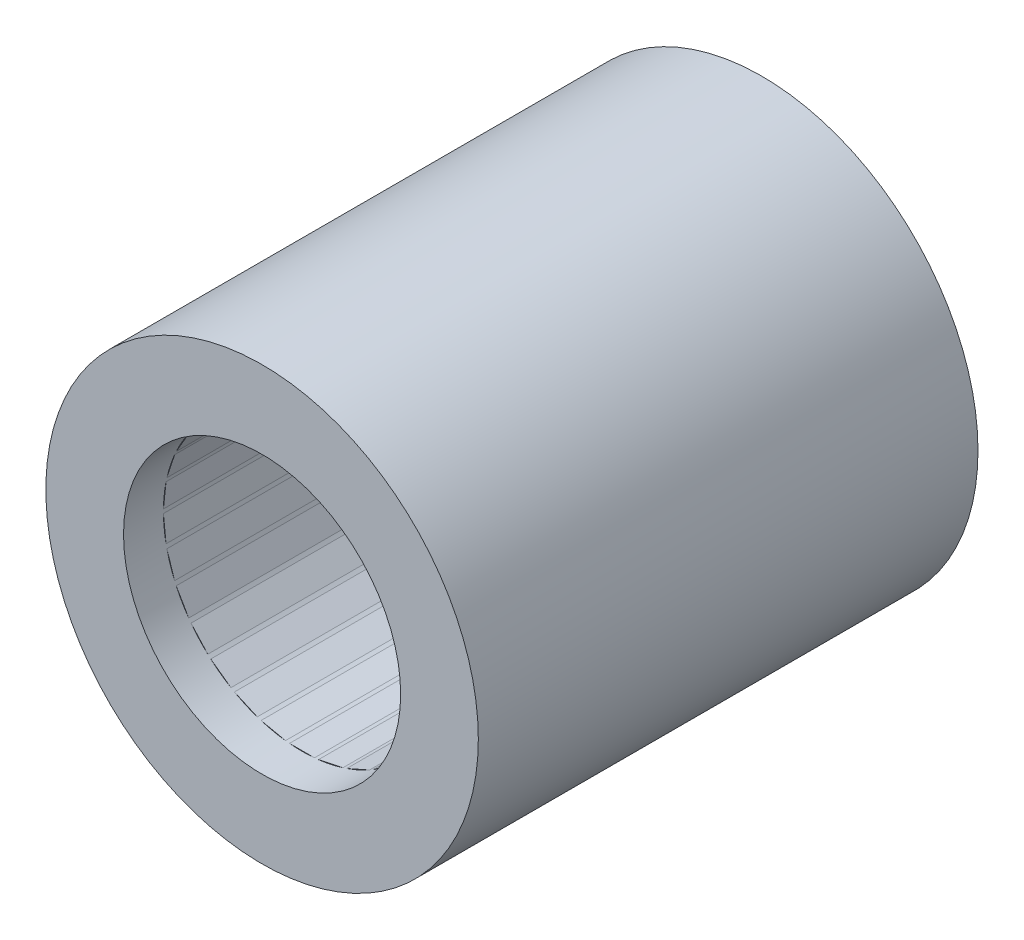
SolidWorks part; units mm, degrees
material "Copper"
ref_plane "Front Plane" through (0, 0, 0) normal (0, 0, 1) x (1, 0, 0)
ref_plane "Top Plane" through (0, 0, 0) normal (0, 1, 0) x (1, 0, 0)
ref_plane "Right Plane" through (0, 0, 0) normal (1, 0, 0) x (0, 0, -1)
sketch "Sketch1" plane through (0, 0, 0) normal (0, 0, 1) x (1, 0, 0)
  circle A0 centre (0, 0) radius 51.5
  circle A1 centre (0, 0) radius 33
extrude "Boss-Extrude1" add sketch "Sketch1" along normal mid plane 119
sketch "Sketch2" plane through (0, 0, 0) normal (0, 0, 1) x (1, 0, 0)
  line L1 (-2.9756, -37.7895) -> (2.9756, -37.7895)
  line L2 (-2.9756, -37.7895) -> (-2.9756, -32.8656)
  line L3 (-2.9756, -32.8656) -> (2.9756, -32.8656)
  line L4 (2.9756, -37.7895) -> (2.9756, -32.8656)
  line L5 (-2.9756, -37.7895) -> (2.9756, -32.8656) construction
  line L6 (-2.9756, -32.8656) -> (2.9756, -37.7895) construction
  circle A0 centre (0, 0) radius 33 construction
  point P0 (0, -35.3276)
extrude "Boss-Extrude2" add sketch "Sketch2" along normal mid plane 100
pattern_circular "CirPattern1" count 30 over 360 about axis through (0, 0, 0) along (0, 0, 1) of "Boss-Extrude2"
